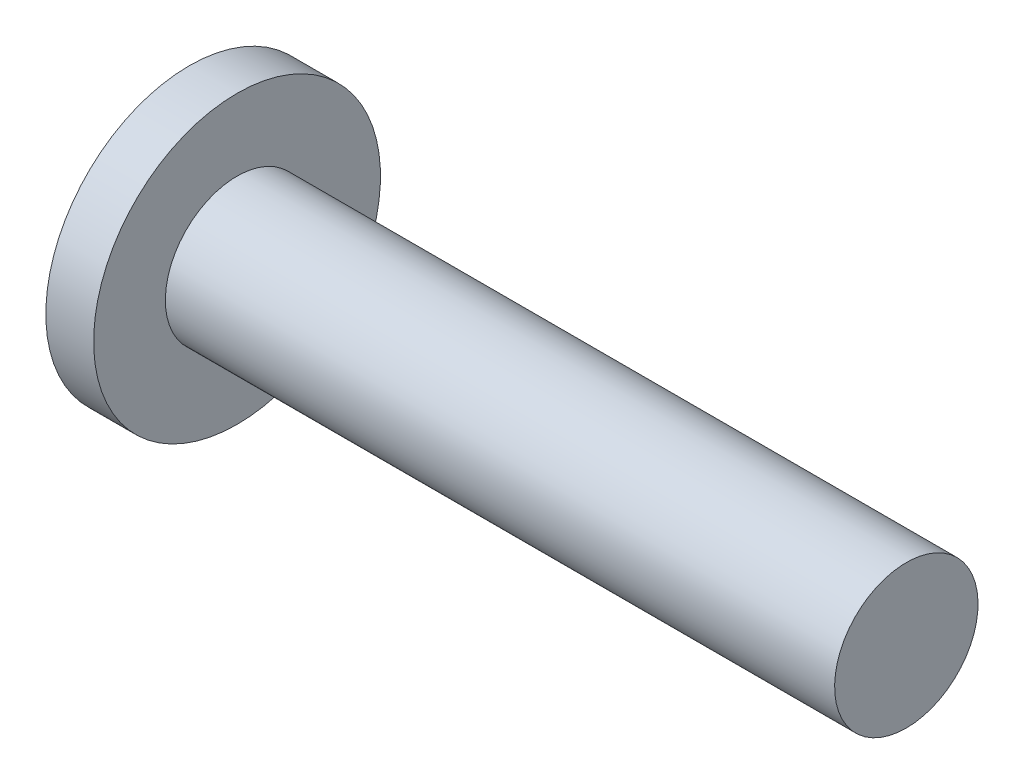
SolidWorks part; units mm, degrees
ref_plane "前视基准面" through (0, 0, 0) normal (0, 0, 1) x (1, 0, 0)
ref_plane "上视基准面" through (0, 0, 0) normal (0, 1, 0) x (1, 0, 0)
ref_plane "右视基准面" through (0, 0, 0) normal (1, 0, 0) x (0, 0, -1)
other "Configuration Table"
sketch "草图1" plane through (0, 0, 0) normal (0, 0, 1) x (1, 0, 0)
  line L0 (0, 0) -> (14, 0)
  line L1 (0, 0) -> (0, 1.5)
  line L2 (0, 1.5) -> (-1, 1.5)
  line L3 (14, 0) -> (14, -1.5)
  line L4 (14, -1.5) -> (12.7823, -1.5) construction
  line L5 (-1, 1.5) -> (-1, -1.5)
  line L6 (-1, -1.5) -> (14, -1.5)
  dimension "D1" = 14
  dimension "D2" = 1.5
  dimension "D3" = 1
  dimension "D4" = 1.5
revolve "旋转1" add sketch "草图1" angle 360 about L6
